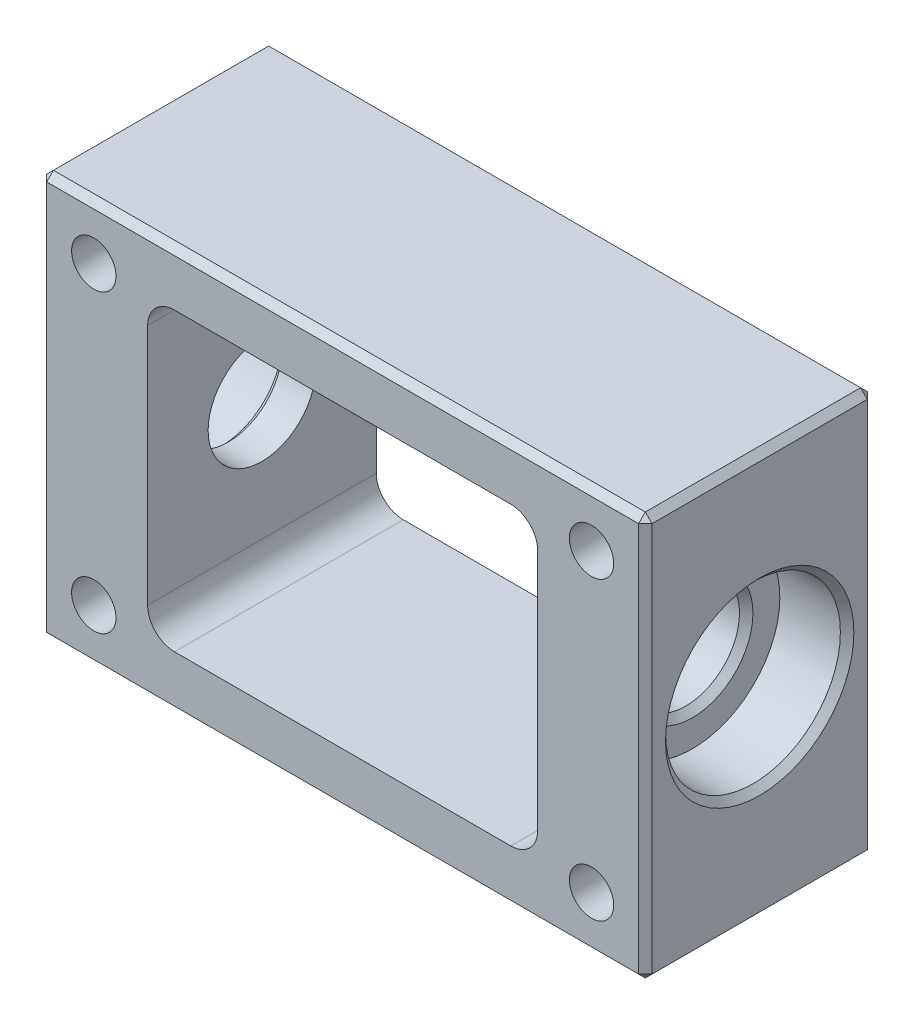
SolidWorks part; units mm, degrees
material "6061 合金"
ref_plane "前视基准面" through (0, 0, 0) normal (0, 0, 1) x (1, 0, 0)
ref_plane "上视基准面" through (0, 0, 0) normal (0, 1, 0) x (1, 0, 0)
ref_plane "右视基准面" through (0, 0, 0) normal (1, 0, 0) x (0, 0, -1)
sketch "草图1" plane through (0, 0, 0) normal (0, 0, 1) x (1, 0, 0)
  line L1 (-22.5, -15) -> (22.5, -15)
  line L2 (-22.5, -15) -> (-22.5, 15)
  line L3 (-22.5, 15) -> (22.5, 15)
  line L4 (22.5, -15) -> (22.5, 15)
  line L5 (0, 15) -> (0, -15) construction
  line L6 (-22.5, 0) -> (22.5, 0) construction
  point P0 (0, 0)
  dimension "D1" = 30
  dimension "D2" = 45
extrude "凸台-拉伸1" add sketch "草图1" along normal mid plane 17
sketch "草图2" plane through (22.5, 0, 0) normal (1, 0, 0) x (0, 0, -1)
  circle A0 centre (0, 0) radius 6.5
  dimension "D1" = 13
extrude "切除-拉伸1" cut sketch "草图2" against normal blind 5
mirror "镜向1" about plane through (0, 0, 0) normal (1, 0, 0) of "切除-拉伸1"
sketch "草图3" plane through (17.5, 0, 0) normal (1, 0, 0) x (0, 0, -1)
  circle A0 centre (0, 0) radius 4
  dimension "D1" = 8
extrude "切除-拉伸2" cut sketch "草图3" against normal blind 53
chamfer "倒角1" distance 0.5 angle 45 4 edges at (17.5, 0, -4) (22.5, 0, -6.5) (-22.5, 0, -6.5) (-17.5, 0, 4)
sketch "草图4" plane through (0, 0, -8.5) normal (0, 0, -1) x (-1, 0, 0)
  line L0 (-22.5, 15) -> (22.5, 15) construction
  line L1 (-18.5, -11) -> (18.5, -11)
  line L2 (-18.5, -11) -> (-18.5, 11)
  line L3 (-18.5, 11) -> (18.5, 11)
  line L4 (18.5, -11) -> (18.5, 11)
  line L5 (0, 11) -> (0, -11) construction
  line L6 (-18.5, 0) -> (18.5, 0) construction
  line L7 (22.5, 15) -> (22.5, -15) construction
  point P0 (0, 0)
  dimension "D1" = 4
  dimension "D2" = 4
hole_wizard "M4 螺纹孔1" positions "草图5" profile "草图6" tap size "M4" standard "GB" end condition through all
sketch "草图5" plane through (0, 0, -8.5) normal (0, 0, -1) x (-1, 0, 0)
  point P0 (-18.5, 11)
  point P3 (18.5, 11)
  point P6 (-18.5, -11)
  point P9 (18.5, -11)
sketch "草图6" plane through (18.5, 11, -8.5) normal (1, 0, 0) x (0, 1, 0)
  line L0 (0, 0) -> (0, 17)
  line L1 (0, 17) -> (1.65, 17)
  line L2 (1.65, 17) -> (1.65, 0)
  line L5 (1.65, 0) -> (0, 0)
  line L11 (0, -6.35) -> (0, 107.95) construction
  dimension "通孔螺纹孔钻头直径" = 3.3
  dimension "通孔螺纹孔钻头深度" = 17
cosmetic thread "孔螺蚊线1" parameters "D2"=4
cosmetic thread "孔螺蚊线2" parameters "D2"=4
cosmetic thread "孔螺蚊线3" parameters "D2"=4
cosmetic thread "孔螺蚊线4" parameters "D2"=4
sketch "草图7" plane through (0, 0, -8.5) normal (0, 0, -1) x (-1, 0, 0)
  line L0 (-22.5, 15) -> (22.5, 15) construction
  line L1 (-14.5, -11) -> (14.5, -11)
  line L2 (-14.5, -11) -> (-14.5, 11)
  line L3 (-14.5, 11) -> (14.5, 11)
  line L4 (14.5, -11) -> (14.5, 11)
  line L5 (0, 11) -> (0, -11) construction
  line L6 (-14.5, 0) -> (14.5, 0) construction
  circle A0 centre (18.5, 11) radius 1.65 construction
  point P0 (0, 0)
  dimension "D1" = 4
  dimension "D2" = 4
extrude "切除-拉伸3" cut sketch "草图7" against normal blind 53
fillet "圆角1" radius 2 4 edges at (-14.5, 11, 0) (-14.5, -11, 0) (14.5, -11, 0) (14.5, 11, 0)
chamfer "倒角2" distance 0.5 angle 45 12 edges at (-22.5, 15, 0) (-22.5, 0, 8.5) (-22.5, 0, -8.5) (-22.5, -15, 0) (0, -15, 8.5) (22.5, -15, 0) (0, -15, -8.5) (0, 15, 8.5) (22.5, 0, 8.5) (22.5, 0, -8.5) (0, 15, -8.5) (22.5, 15, 0)
